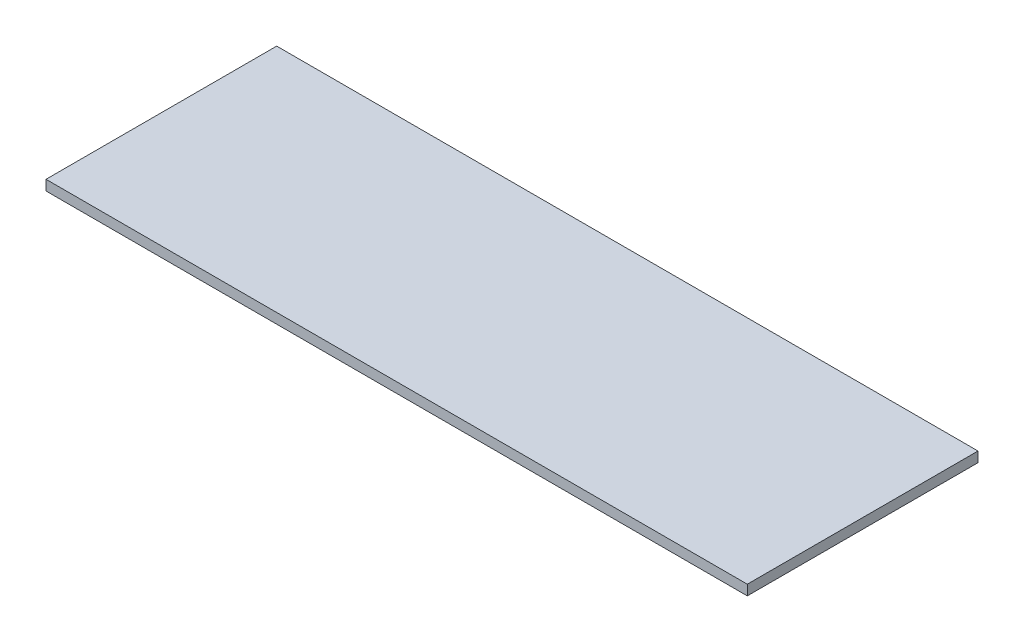
SolidWorks part; units mm, degrees
material "玻璃"
ref_plane "前视基准面" through (0, 0, 0) normal (0, 0, 1) x (1, 0, 0)
ref_plane "上视基准面" through (0, 0, 0) normal (0, 1, 0) x (1, 0, 0)
ref_plane "右视基准面" through (0, 0, 0) normal (1, 0, 0) x (0, 0, -1)
sketch "草图1" plane through (0, 0, 0) normal (0, 1, 0) x (1, 0, 0)
  line L1 (-38, 12.5) -> (38, 12.5)
  line L2 (-38, 12.5) -> (-38, -12.5)
  line L3 (-38, -12.5) -> (38, -12.5)
  line L4 (38, 12.5) -> (38, -12.5)
  line L5 (-38, 12.5) -> (38, -12.5) construction
  line L6 (-38, -12.5) -> (38, 12.5) construction
  point P0 (0, 0)
  dimension "D1" = 76
  dimension "D2" = 25
extrude "凸台-拉伸1" add sketch "草图1" along normal blind 1.1
